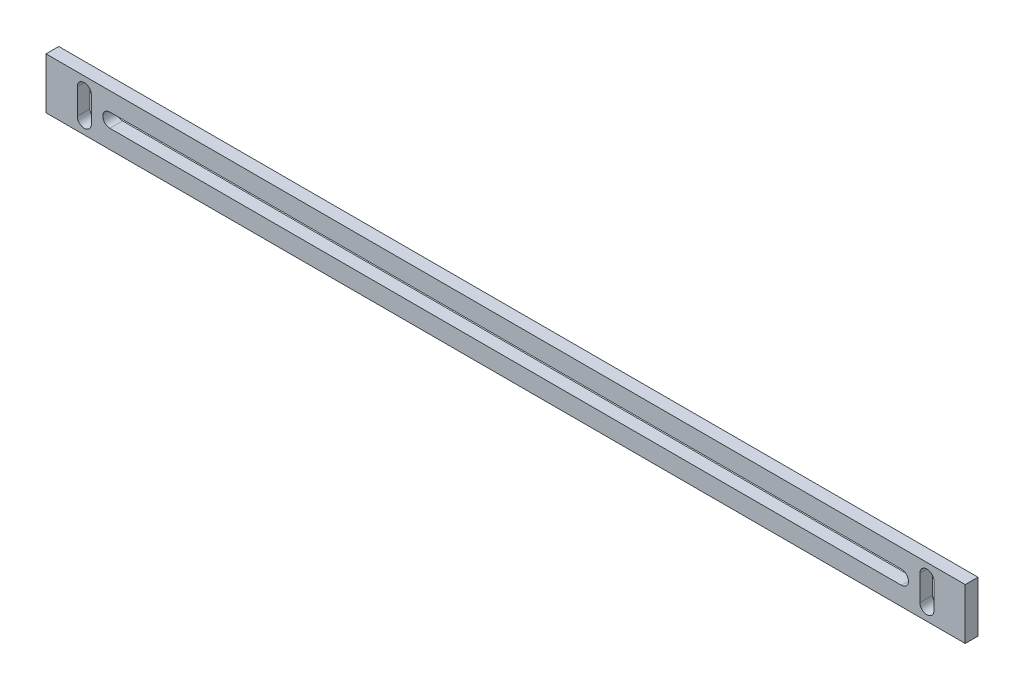
SolidWorks part; units mm, degrees
material "ABS"
ref_plane "前视基准面" through (0, 0, 0) normal (0, 0, 1) x (1, 0, 0)
ref_plane "上视基准面" through (0, 0, 0) normal (0, 1, 0) x (1, 0, 0)
ref_plane "右视基准面" through (0, 0, 0) normal (1, 0, 0) x (0, 0, -1)
other "Configuration Table"
sketch "草图1" plane through (0, 0, 0) normal (0, 0, 1) x (1, 0, 0)
  line L0 (0, 0) -> (0, 10)
  line L1 (0, 10) -> (-175, 10)
  line L2 (-175, 10) -> (-175, -10)
  line L3 (-175, -10) -> (175, -10)
  line L4 (175, -10) -> (175, 10)
  line L5 (175, 10) -> (0, 10)
extrude "凸台-拉伸1" add sketch "草图1" along normal blind 5
sketch "草图3" plane through (0, 0, 0) normal (0, 0, -1) x (-1, 0, 0)
  line L0 (-175, 0) -> (-165, 0)
  line L1 (-175, -10) -> (-175, 10) construction
  line L2 (-165, 0) -> (-165, 10)
  line L3 (-175, 10) -> (175, 10) construction
  line L4 (-165, 0) -> (-165, -10)
  line L5 (175, -10) -> (-175, -10) construction
  line L6 (-165, 0) -> (-155, 0)
  line L7 (175, 0) -> (165, 0)
  line L8 (175, 10) -> (175, -10) construction
  line L9 (165, 0) -> (165, 10)
  line L10 (165, 0) -> (165, -10)
  line L11 (165, 0) -> (155, 0)
  line L12 (155, 0) -> (-155, 0)
  line L13 (-155, 0) -> (155, 0) construction
  line L14 (-155, 2.75) -> (155, 2.75)
  line L15 (-155, -2.75) -> (155, -2.75)
  line L16 (-165, 0) -> (-165, -5)
  line L17 (-165, -5) -> (-165, 5)
  line L18 (165, -5) -> (165, 5)
  line L19 (-165, -5) -> (-165, 5) construction
  line L20 (-167.75, -5) -> (-167.75, 5)
  line L21 (-162.25, -5) -> (-162.25, 5)
  line L22 (165, -5) -> (165, 5) construction
  line L23 (162.25, -5) -> (162.25, 5)
  line L24 (167.75, -5) -> (167.75, 5)
  arc A0 (-155, 2.75) -> (-155, -2.75) centre (-155, 0) ccw
  arc A1 (155, -2.75) -> (155, 2.75) centre (155, 0) ccw
  arc A2 (-167.75, -5) -> (-162.25, -5) centre (-165, -5) ccw
  arc A3 (-162.25, 5) -> (-167.75, 5) centre (-165, 5) ccw
  arc A4 (162.25, -5) -> (167.75, -5) centre (165, -5) ccw
  arc A5 (167.75, 5) -> (162.25, 5) centre (165, 5) ccw
  point P19 (0, 0)
  point P28 (-165, 0)
  point P33 (165, 0)
  dimension "D1" = 10
  dimension "D2" = 10
  dimension "D3" = 10
  dimension "D4" = 10
extrude "切除-拉伸1" cut sketch "草图3" against normal blind 5 contours L21 A3 L2 L6 | L2 A3 L20 L0 | L20 A2 L4 L0 | L4 A2 L21 L6 | L15 A1 L11 L12 L6 A0 | L11 A1 L14 A0 L6 L12 | L24 A5 L9 L7 | L9 A5 L23 L11 | L23 A4 L10 L11 | L10 A4 L24 L7
sketch "草图4" plane through (0, 0, 0) normal (0, 0, -1) x (-1, 0, 0)
  line L0 (-175, -10) -> (-180, -10)
  line L1 (-180, -10) -> (-180, 10)
  line L2 (-180, 10) -> (-175, 10)
  line L3 (-175, 10) -> (-175, -10)
  line L4 (175, -10) -> (180, -10)
  line L5 (180, -10) -> (180, 10)
  line L6 (180, 10) -> (175, 10)
  line L7 (175, 10) -> (175, -10)
extrude "凸台-拉伸2" add sketch "草图4" against normal blind 5
